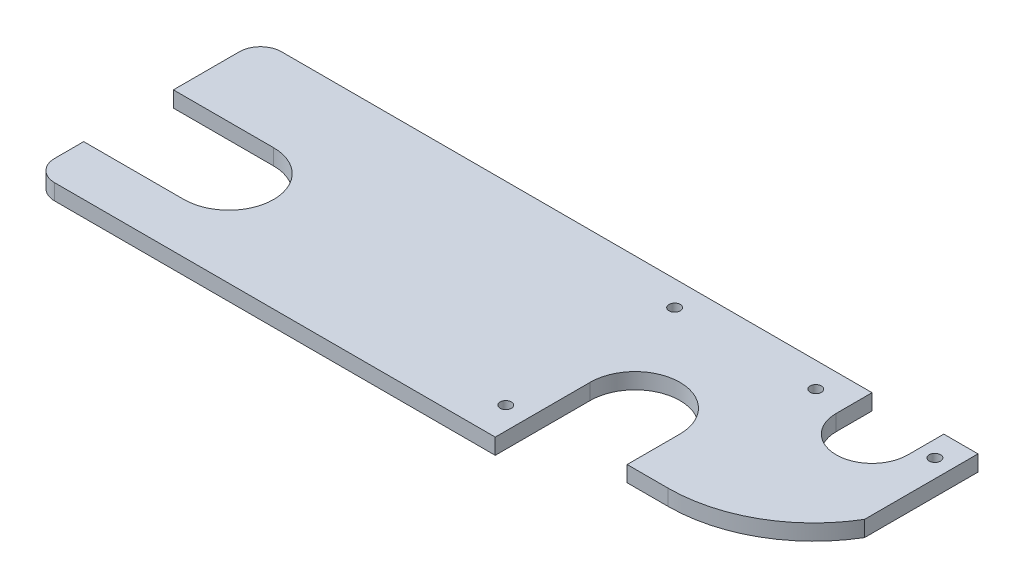
SolidWorks part; units mm, degrees
material "PC High Viscosity"
ref_plane "Front Plane" through (0, 0, 0) normal (0, 0, 1) x (1, 0, 0)
ref_plane "Top Plane" through (0, 0, 0) normal (0, 1, 0) x (1, 0, 0)
ref_plane "Right Plane" through (0, 0, 0) normal (1, 0, 0) x (0, 0, -1)
sketch "Sketch1" plane through (0, 0, 0) normal (0, 1, 0) x (1, 0, 0)
  line L1 (25.4, 0) -> (277.8125, 0)
  line L3 (12.7, 136.525) -> (23.8125, 136.525)
  line L4 (431.8, 0) -> (431.8, 136.525) construction
  line L6 (182.5625, 0) -> (182.5625, 117.943) construction
  line L7 (277.8125, 57.15) -> (277.8125, 0)
  line L8 (331.7875, 57.15) -> (331.7875, 0)
  line L9 (368.046, 114.935) -> (368.046, 136.525)
  line L10 (411.226, 114.935) -> (411.226, 136.525)
  line L11 (411.226, 136.525) -> (431.8, 136.525)
  line L12 (331.7875, 0) -> (431.8, 0) construction
  line L13 (23.8125, 136.525) -> (368.046, 136.525)
  line L14 (331.7875, 0) -> (357.1875, 0)
  line L15 (431.8, 136.525) -> (431.8, 68.2625)
  line L16 (60.325, 30.1625) -> (22.225, 30.1625)
  line L17 (0, 17.4625) -> (0, 12.7)
  line L18 (12.7, 0) -> (25.4, 0)
  line L19 (60.325, 84.1375) -> (22.225, 84.1375)
  line L20 (0, 96.8375) -> (0, 123.825)
  line L21 (22.225, 84.1375) -> (0, 84.1375)
  line L22 (0, 84.1375) -> (0, 96.8375)
  line L23 (22.225, 30.1625) -> (0, 30.1625)
  line L24 (0, 30.1625) -> (0, 17.4625)
  arc A0 (60.325, 30.1625) -> (87.3125, 57.15) centre (60.325, 57.15) ccw
  arc A1 (277.8125, 57.15) -> (331.7875, 57.15) centre (304.8, 57.15) cw
  arc A2 (368.046, 114.935) -> (411.226, 114.935) centre (389.636, 114.935) ccw
  arc A3 (357.1875, 0) -> (431.8, 68.2625) centre (357.1875, 74.9078) ccw
  arc A5 (60.325, 84.1375) -> (87.3125, 57.15) centre (60.325, 57.15) cw
  arc A6 (0, 12.7) -> (12.7, 0) centre (12.7, 12.7) ccw
  arc A8 (0, 123.825) -> (12.7, 136.525) centre (12.7, 123.825) cw
  point P27 (0, 0)
  point P35 (0, 0)
  point P40 (0, 136.525)
  dimension "D3" = 53.975
  dimension "D4" = 12.7
  dimension "D5" = 57.15
  dimension "D8" = 43.18
  dimension "D12" = 21.59
  dimension "D14" = 12.7
  dimension "D15" = 74.9078
  dimension "D1" = 431.8
  dimension "D2" = 136.525
  dimension "D6" = 122.2375
  dimension "D7" = 244.475
  dimension "D9" = 42.164
  dimension "D10" = 127
  dimension "D11" = 25.4
  dimension "D13" = 136.525
  dimension "D16" = 57.15
  dimension "D17" = 57.15
extrude "Boss-Extrude2" add sketch "Sketch1" along normal blind 9.525 contours L13 L9 A2 L10 L11 L15 A3 L14 L8 A1 L7 L1 L18 A6 L17 L24 L23 L16 A0 A5 L19 L21 L22 L20 A8 L3
sketch "Sketch2" plane through (0, 9.525, 0) normal (0, 1, 0) x (1, 0, 0)
  line L0 (331.7875, 0) -> (331.7875, 25.4)
  line L5 (431.8, 136.525) -> (431.8, 68.2625) construction
  line L21 (331.7875, 25.4) -> (356.3938, 25.4)
  line L22 (331.7875, 57.15) -> (331.7875, 0) construction
  line L23 (331.7875, 0) -> (357.1875, 0) construction
  line L25 (331.7875, 0) -> (357.1875, 0)
  arc A2 (356.3938, 25.4) -> (431.8, 68.2625) centre (356.3938, 113.1608) ccw
  arc A3 (357.1875, 0) -> (431.8, 68.2625) centre (357.1875, 74.9078) ccw
  dimension "D3" = 25.4
extrude "Cut-Extrude2" cut sketch "Sketch2" against normal through all
hole_wizard "1/4 Clearance Hole1" positions "Sketch3" profile "Sketch4" hole size "1/4" standard "ANSI Inch" end condition through all
sketch "Sketch3" plane through (0, 9.525, 0) normal (0, 1, 0) x (1, 0, 0)
  line L1 (12.7, 136.525) -> (368.046, 136.525) construction
  line L6 (304.8, 84.1375) -> (304.8, 136.525) construction
  line L10 (431.8, 136.525) -> (431.8, 68.2625) construction
  line L11 (12.7, 136.525) -> (368.046, 136.525) construction
  line L13 (368.046, 114.935) -> (368.046, 136.525) construction
  line L14 (12.7, 0) -> (277.8125, 0) construction
  line L15 (277.8125, 57.15) -> (277.8125, 0) construction
  arc A0 (331.7875, 57.15) -> (277.8125, 57.15) centre (304.8, 57.15) ccw construction
  point P0 (420.9542, 121.4438)
  point P2 (349.269, 121.4438)
  point P4 (264.3188, 121.4438)
  point P6 (264.3188, 19.8438)
  dimension "D1" = 10.8458
  dimension "D2" = 15.0812
  dimension "D3" = 40.4812
  dimension "D4" = 18.777
  dimension "D5" = 19.8438
  dimension "D6" = 13.4938
sketch "Sketch4" plane through (420.9542, 9.525, -121.4438) normal (1, 0, 0) x (0, 0, 1)
  line L0 (0, 0) -> (0, 9.525)
  line L1 (0, 9.525) -> (3.3782, 9.525)
  line L2 (3.3782, 9.525) -> (3.3782, 0)
  line L5 (3.3782, 0) -> (0, 0)
  line L11 (0, -6.35) -> (0, 107.95) construction
  dimension "Thru Hole Dia." = 6.7564
  dimension "Thru Hole Depth" = 9.525
fillet "Fillet5" [suppressed] radius 23.8125
fillet "Fillet6" [suppressed] radius 12.7
fillet "Fillet7" [suppressed] radius 6.35
